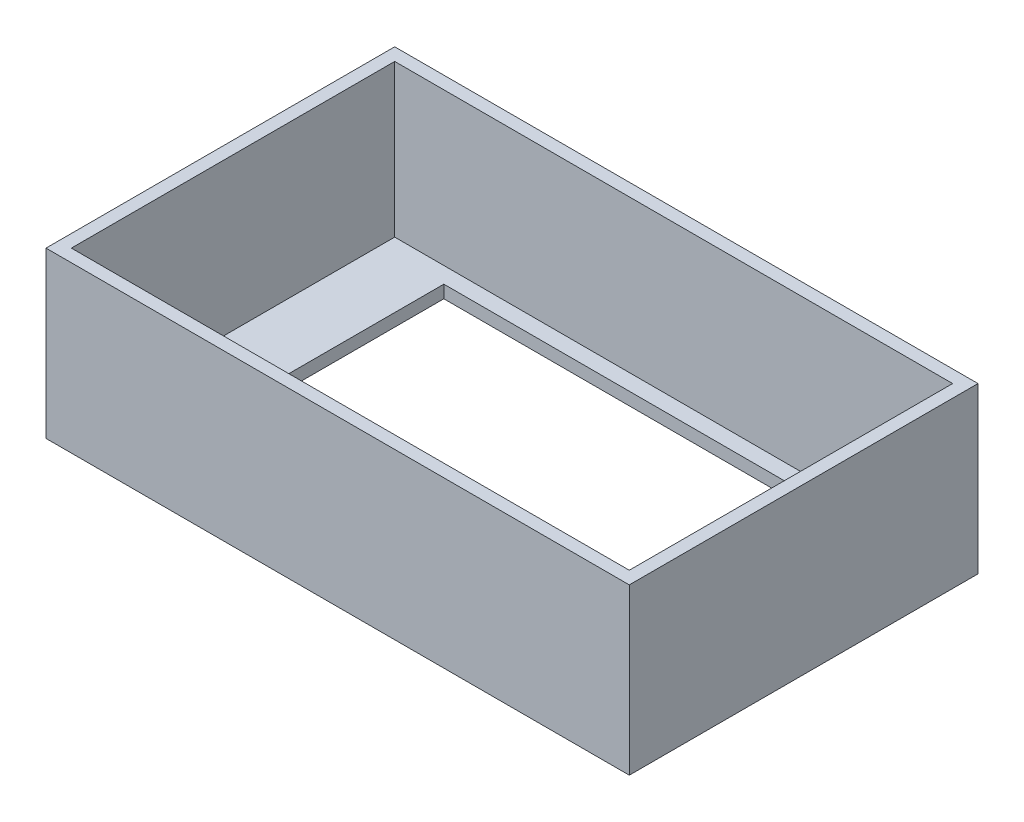
SolidWorks part; units mm, degrees
ref_plane "Front Plane" through (0, 0, 0) normal (0, 0, 1) x (1, 0, 0)
ref_plane "Top Plane" through (0, 0, 0) normal (0, 1, 0) x (1, 0, 0)
ref_plane "Right Plane" through (0, 0, 0) normal (1, 0, 0) x (0, 0, -1)
sketch "Sketch1" plane through (0, 0, 0) normal (0, 1, 0) x (1, 0, 0)
  line L0 (0, -55) -> (0, 55) construction
  line L1 (-44, 25.5) -> (44, 25.5)
  line L2 (-44, 25.5) -> (-44, -25.5)
  line L3 (-44, -25.5) -> (44, -25.5)
  line L4 (44, 25.5) -> (44, -25.5)
  line L5 (-55, 0) -> (55, 0) construction
  point P4 (0, 25.5)
  point P7 (44, 0)
  dimension "D1" = 88
  dimension "D2" = 51
sketch "Sketch2" plane through (0, 0, 0) normal (0, 1, 0) x (1, 0, 0)
  line L0 (-44, 25.5) -> (-44, -25.5) construction
  line L1 (-33.7, 22.95) -> (26.5, 22.95)
  line L2 (-33.7, 22.95) -> (-33.7, -22.95)
  line L3 (-33.7, -22.95) -> (26.5, -22.95)
  line L4 (26.5, 22.95) -> (26.5, -22.95)
  line L5 (-44, 25.5) -> (44, 25.5) construction
  line L6 (-48.4, 0) -> (48.4, 0) construction
  line L7 (44, 25.5) -> (44, -25.5) construction
  point P8 (-33.7, 0)
  dimension "D1" = 10.3
  dimension "D2" = 2.55
  dimension "D3" = 17.5
extrude "Boss-Extrude1" add sketch "Sketch1" along normal blind 2
extrude "Cut-Extrude1" cut sketch "Sketch2" along normal up to surface (2 mm away) up to face at (0, 2, 0)
sketch "Sketch3" plane through (0, 0, 0) normal (0, 1, 0) x (1, 0, 0)
  line L0 (-46, 27.5) -> (-46, -27.5)
  line L1 (-46, -27.5) -> (46, -27.5)
  line L2 (46, -27.5) -> (46, 27.5)
  line L3 (46, 27.5) -> (-46, 27.5)
  line L4 (44, 25.5) -> (-44, 25.5)
  line L5 (44, -25.5) -> (44, 25.5)
  line L6 (-44, -25.5) -> (44, -25.5)
  line L7 (-44, 25.5) -> (-44, -25.5)
  line L8 (44, 25.5) -> (-44, 25.5)
  line L9 (44, -25.5) -> (44, 25.5)
  line L10 (-44, -25.5) -> (44, -25.5)
  line L11 (-44, 25.5) -> (-44, -25.5)
  dimension "D1" = 0
  dimension "D2" = 2
extrude "Boss-Extrude2" add sketch "Sketch3" along normal blind 26
sketch "Sketch4" plane through (0, 2, 0) normal (0, 1, 0) x (1, 0, 0)
  line L0 (-33.7, 22.95) -> (-33.7, -22.95) construction
  line L1 (-42.7, 22.65) -> (-38.2, 22.65) construction
  line L2 (-42.7, 22.65) -> (-42.7, 18.15) construction
  line L3 (-42.7, 18.15) -> (-38.2, 18.15) construction
  line L4 (-38.2, 22.65) -> (-38.2, 18.15) construction
  line L6 (26.5, 22.95) -> (-33.7, 22.95) construction
  circle A0 centre (-40.45, 20.4) radius 2.25
  point P6 (-43.0892, 24.7051)
  point P9 (-38.2, 22.709)
  point P10 (-38.2, 16.7568)
  dimension "D3" = 4.5
  dimension "D1" = 4.5
  dimension "D2" = 0.3
